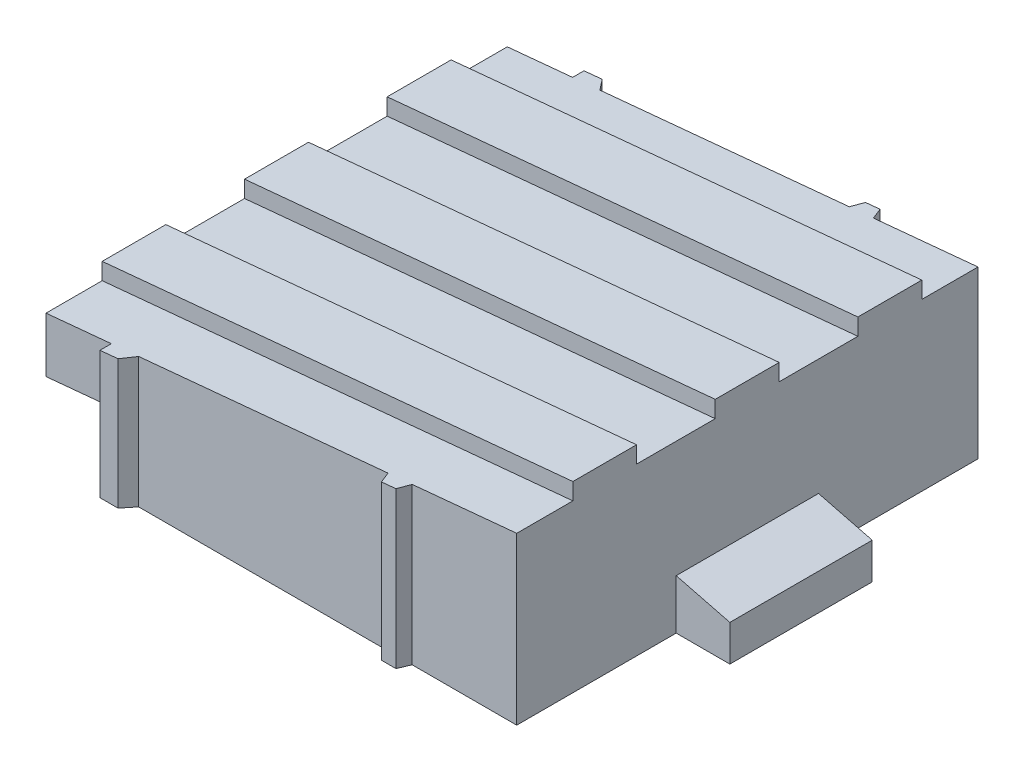
SolidWorks part; units mm, degrees
ref_plane "Front Plane" through (0, 0, 0) normal (0, 0, 1) x (1, 0, 0)
ref_plane "Top Plane" through (0, 0, 0) normal (0, 1, 0) x (1, 0, 0)
ref_plane "Right Plane" through (0, 0, 0) normal (1, 0, 0) x (0, 0, -1)
sketch "Sketch1" plane through (0, 0, 0) normal (0, 0, 1) x (1, 0, 0)
  line L0 (-87.1281, -11.0306) -> (-72.5481, -11.0306)
  line L1 (-72.5481, -11.0306) -> (-72.5481, -4.4506)
  line L3 (-72.5481, -4.4506) -> (-85.741, -5.7035)
  line L4 (-85.741, -5.7035) -> (-89.4781, -6.0583)
  line L5 (-89.4781, -6.0583) -> (-89.4781, -8.6383)
  line L6 (-89.4781, -8.6383) -> (-87.1281, -8.4152)
  line L7 (-87.1281, -8.4152) -> (-87.1281, -11.0306)
  dimension "D1" = 5.425
  dimension "D2" = 6.58
  dimension "D3" = 16.93
  dimension "D4" = 14.58
  dimension "D5" = 2.58
extrude "Boss-Extrude1" add sketch "Sketch1" along normal blind 16.59 contours L3 L4 L5 L6 L7 L0 L1
sketch "Sketch6" plane through (0, -11.0306, 0) normal (0, -1, 0) x (1, 0, 0)
  line L0 (-87.1281, 16.59) -> (-87.1281, 17)
  line L1 (-87.1281, 17) -> (-86.4747, 17)
  line L2 (-86.4747, 17) -> (-86.1481, 16.59)
  line L3 (-87.1281, 16.59) -> (-72.5481, 16.59) construction
  line L4 (-77.1781, 16.59) -> (-77.0041, 17)
  line L5 (-77.0041, 17) -> (-76.4821, 17)
  line L6 (-76.4821, 17) -> (-76.3081, 16.59)
  line L7 (-87.1281, 0) -> (-87.1281, -0.41)
  line L8 (-87.1281, -0.41) -> (-86.4747, -0.41)
  line L9 (-86.4747, -0.41) -> (-86.1481, 0)
  line L10 (-87.1281, 0) -> (-72.5481, 0) construction
  line L11 (-77.1781, 0) -> (-77.0041, -0.41)
  line L12 (-77.0041, -0.41) -> (-76.4821, -0.41)
  line L13 (-76.4821, -0.41) -> (-76.3081, 0)
  line L14 (-77.1781, 16.59) -> (-76.3081, 16.59)
  line L15 (-87.1281, 16.59) -> (-86.1481, 16.59)
  line L16 (-87.1281, 0) -> (-86.1481, 0)
  line L17 (-77.1781, 0) -> (-76.3081, 0)
  dimension "D1" = 0.41
  dimension "D2" = 0.41
  dimension "D3" = 0.98
  dimension "D4" = 0.6533
  dimension "D5" = 0.87
  dimension "D6" = 0.174
  dimension "D7" = 0.522
  dimension "D8" = 3.76
extrude "Boss-Extrude2" add sketch "Sketch6" against normal blind 6
sketch "Sketch4" plane through (-0.2295, 2.4168, 0) normal (-0.0945, 0.9955, 0) x (0.9955, 0.0945, 0)
  line L1 (-72.6439, 2.02) -> (-90.2157, 2.02)
  line L2 (-72.6439, 2.02) -> (-72.6439, -2.02)
  line L3 (-72.6439, -2.02) -> (-90.2157, -2.02)
  line L4 (-90.2157, 2.02) -> (-90.2157, -2.02)
  line L6 (-72.6439, -18.61) -> (-90.2157, -18.61)
  line L7 (-72.6439, -18.61) -> (-72.6439, -14.57)
  line L8 (-72.6439, -14.57) -> (-90.2157, -14.57)
  line L9 (-90.2157, -18.61) -> (-90.2157, -14.57)
  line L10 (-72.6439, -4.32) -> (-90.2157, -4.32)
  line L11 (-72.6439, -4.32) -> (-72.6439, -7.15)
  line L12 (-72.6439, -7.15) -> (-90.2157, -7.15)
  line L13 (-90.2157, -4.32) -> (-90.2157, -7.15)
  line L15 (-72.6439, -9.45) -> (-90.2157, -9.45)
  line L16 (-72.6439, -9.45) -> (-72.6439, -12.28)
  line L17 (-72.6439, -12.28) -> (-90.2157, -12.28)
  line L18 (-90.2157, -9.45) -> (-90.2157, -12.28)
  line L19 (-89.6501, -16.59) -> (-89.6501, 0) construction
  point P4 (-72.6439, -16.59)
  point P11 (-72.6439, 0)
  point P22 (0, 0)
  point P23 (-89.6501, -16.59)
  dimension "D1" = 4.04
  dimension "D2" = 4.04
  dimension "D3" = 2.3
  dimension "D4" = 2.83
  dimension "D5" = 2.3
  dimension "D6" = 2.83
  dimension "D7" = 0.5656
extrude "Cut-Extrude1" cut sketch "Sketch4" against normal blind 0.6
sketch "Sketch7" plane through (0, -5.0306, 0) normal (0, 1, 0) x (1, 0, 0)
  line L0 (-87.1281, -17) -> (-86.4747, -17)
  line L1 (-86.4747, -17) -> (-86.1481, -16.59)
  line L2 (-87.1281, -16.59) -> (-86.1481, -16.59) construction
  line L3 (-86.1481, -16.59) -> (-86.4747, -17) construction
  line L4 (-86.1481, -16.59) -> (-87.1281, -16.59)
  line L5 (-87.1281, -16.59) -> (-87.1281, -17)
  line L6 (-87.1281, 0) -> (-87.1281, 0.41)
  line L7 (-87.1281, 0.41) -> (-86.4747, 0.41)
  line L8 (-86.4747, 0.41) -> (-86.1481, 0)
  line L9 (-86.1481, 0) -> (-87.1281, 0)
extrude "Cut-Extrude2" cut sketch "Sketch7" against normal blind 1
sketch "Sketch8" plane through (-72.5481, 0, 0) normal (1, 0, 0) x (0, 0, -1)
  line L0 (-16.59, -11.0306) -> (0, -11.0306) construction
  line L1 (-10.855, -11.0306) -> (-5.735, -11.0306)
  line L2 (-10.855, -11.0306) -> (-10.855, -9.2406)
  line L3 (-10.855, -9.2406) -> (-5.735, -9.2406)
  line L4 (-5.735, -11.0306) -> (-5.735, -9.2406)
  point P6 (-8.295, -11.0306)
  point P7 (-8.295, -11.0306)
  dimension "D1" = 5.12
  dimension "D2" = 1.79
extrude "Boss-Extrude3" add sketch "Sketch8" along normal blind 1.93
sketch "Sketch9" plane through (0, 0, 10.855) normal (0, 0, 1) x (1, 0, 0)
  line L0 (-70.6181, -9.7306) -> (-72.5481, -9.2406)
  line L1 (-70.6181, -9.2406) -> (-70.6181, -11.0306) construction
  line L2 (-70.6181, -9.2406) -> (-72.5481, -9.2406) construction
  line L3 (-72.5481, -9.2406) -> (-70.6181, -9.2406)
  line L4 (-70.6181, -9.2406) -> (-70.6181, -9.7306)
  line L5 (-70.6181, -11.0306) -> (-72.5481, -11.0306) construction
  dimension "D1" = 1.3
extrude "Cut-Extrude4" cut sketch "Sketch9" against normal up to next
sketch "Sketch10" plane through (0, -11.0306, 0) normal (0, -1, 0) x (1, 0, 0)
  line L0 (-74.0581, 15.2033) -> (-85.6181, 15.2033)
  line L1 (-85.6181, 15.2033) -> (-85.6181, 11.34)
  line L2 (-85.6181, 11.34) -> (-87.1281, 11.34)
  line L3 (-87.1281, 17) -> (-87.1281, -0.41) construction
  line L4 (-87.1281, 11.34) -> (-87.1281, 5.25)
  line L5 (-87.1281, 5.25) -> (-85.6181, 5.25)
  line L6 (-85.6181, 5.25) -> (-85.6181, 1.28)
  line L7 (-85.6181, 1.28) -> (-74.0581, 1.28)
  line L8 (-74.0581, 15.2033) -> (-74.0581, 1.28)
  line L10 (-72.5481, 5.735) -> (-72.5481, 0) construction
  line L11 (-72.5481, 16.59) -> (-72.5481, 10.855) construction
  line L12 (-86.1481, 0) -> (-77.1781, 0) construction
  line L13 (-86.1481, 16.59) -> (-77.1781, 16.59) construction
  point P18 (0, 0)
  dimension "D1" = 11.56
  dimension "D2" = 11.56
  dimension "D3" = 1.51
  dimension "D4" = 1.51
  dimension "D5" = 1.28
  dimension "D6" = 1.3867
  dimension "D7" = 5.66
  dimension "D8" = 5.66
extrude "Cut-Extrude5" cut sketch "Sketch10" against normal offset from surface (3.8952 mm away) 1.93
sketch "Sketch11" plane through (-89.4781, 0, 0) normal (-1, 0, 0) x (0, 0, 1)
  line L0 (16.59, -8.6383) -> (0, -8.6383) construction
  line L1 (10.445, -8.6383) -> (6.145, -8.6383)
  line L2 (10.445, -8.6383) -> (10.445, -15.5383)
  line L3 (10.445, -15.5383) -> (6.145, -15.5383)
  line L4 (6.145, -8.6383) -> (6.145, -15.5383)
  point P6 (8.295, -8.6383)
  point P7 (8.295, -8.6383)
  dimension "D1" = 4.3
  dimension "D2" = 6.9
extrude "Boss-Extrude4" add sketch "Sketch11" against normal blind 1.22 separate body
sketch "Sketch12" plane through (0, 0, 6.145) normal (0, 0, -1) x (-1, 0, 0)
  line L0 (89.4781, -15.5383) -> (89.8081, -14.4683)
  line L1 (89.8081, -14.4683) -> (89.4781, -14.4683)
  line L2 (89.4781, -8.6383) -> (89.4781, -15.5383) construction
  line L3 (89.4781, -14.4683) -> (89.4781, -15.5383)
  dimension "D1" = 0.33
  dimension "D2" = 1.07
extrude "Boss-Extrude5" add sketch "Sketch12" against normal up to surface (4.3 mm away) up to face at (-88.8681, -12.0883, 10.445)
equation "\"tabH\"=2.3"
equation "\"TabL\"=2.83"
equation "\"tabEdge\"=4.04"
equation "\"D1@Sketch4\"=\"tabEdge\""
equation "\"D2@Sketch4\"=\"tabEdge\""
equation "\"D3@Sketch4\"=\"tabH\""
equation "\"D4@Sketch4\"=\"TabL\""
equation "\"D5@Sketch4\"=\"tabH\""
equation "\"D6@Sketch4\"=\"TabL\""
equation "\"sidebumpheight\"=0.41"
equation "\"D1@Sketch6\"=\"sidebumpheight\""
equation "\"D2@Sketch6\"=\"sidebumpheight\""
equation "\"IDfb\"=11.56"
equation "\"D1@Sketch10\"=\"IDfb\""
equation "\"D2@Sketch10\"=\"IDfb\""
